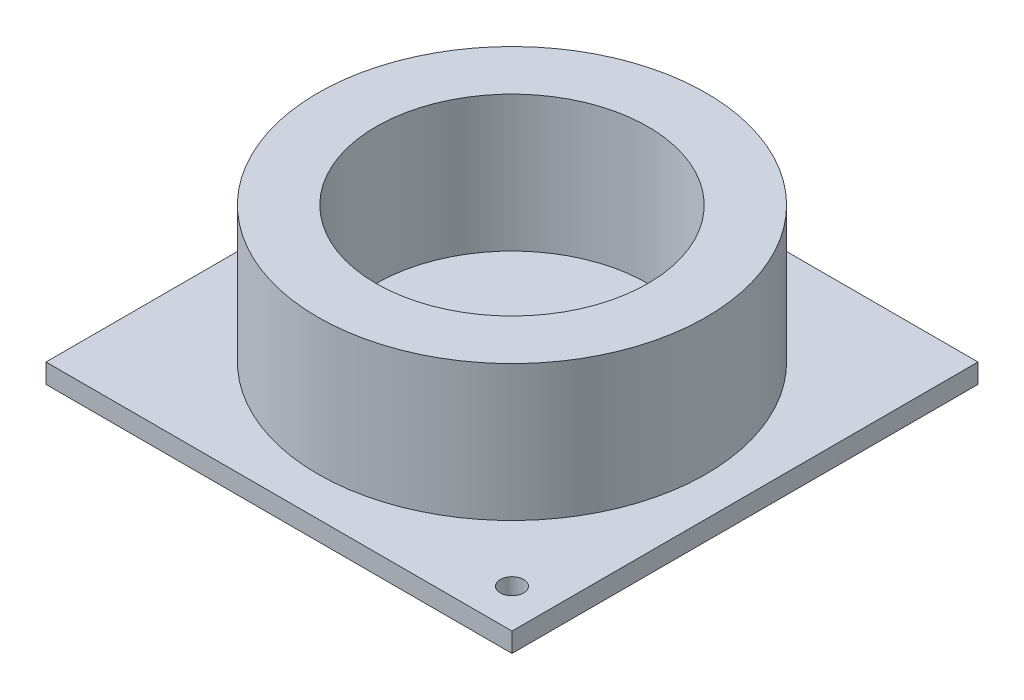
SolidWorks part; units mm, degrees
ref_plane "Front Plane" through (0, 0, 0) normal (0, 0, 1) x (1, 0, 0)
ref_plane "Top Plane" through (0, 0, 0) normal (0, 1, 0) x (1, 0, 0)
ref_plane "Right Plane" through (0, 0, 0) normal (1, 0, 0) x (0, 0, -1)
sketch "Sketch1" plane through (0, 0, 0) normal (0, 1, 0) x (1, 0, 0)
  circle A0 centre (0, 0) radius 50
  circle A1 centre (0, 0) radius 35
  dimension "D1" = 70
  dimension "D2" = 100
extrude "Boss-Extrude1" add sketch "Sketch1" along normal blind 40
sketch "Sketch2" plane through (0, 0, 0) normal (0, 1, 0) x (1, 0, 0)
  line L1 (-60, 60) -> (60, 60)
  line L2 (-60, 60) -> (-60, -60)
  line L3 (-60, -60) -> (60, -60)
  line L4 (60, 60) -> (60, -60)
  line L5 (-60, 60) -> (60, -60) construction
  line L6 (-60, -60) -> (60, 60) construction
  point P0 (0, 0)
  dimension "D1" = 120
  dimension "D2" = 120
extrude "Boss-Extrude2" add sketch "Sketch2" along normal blind 5
sketch "Sketch3" plane through (0, 5, 0) normal (0, 1, 0) x (1, 0, 0)
  line L0 (60, 60) -> (-60, 60) construction
  line L1 (-60, 60) -> (-60, -60) construction
  line L2 (-60, -60) -> (60, -60) construction
  line L3 (60, -60) -> (60, 60) construction
  circle A0 centre (-50, 50) radius 3
  circle A1 centre (50, -50) radius 3
  point P8 (0, 0)
  dimension "D1" = 6
  dimension "D4" = 6
  dimension "D2" = 10
  dimension "D3" = 10
  dimension "D5" = 10
  dimension "D6" = 10
extrude "Cut-Extrude1" cut sketch "Sketch3" against normal blind 5
